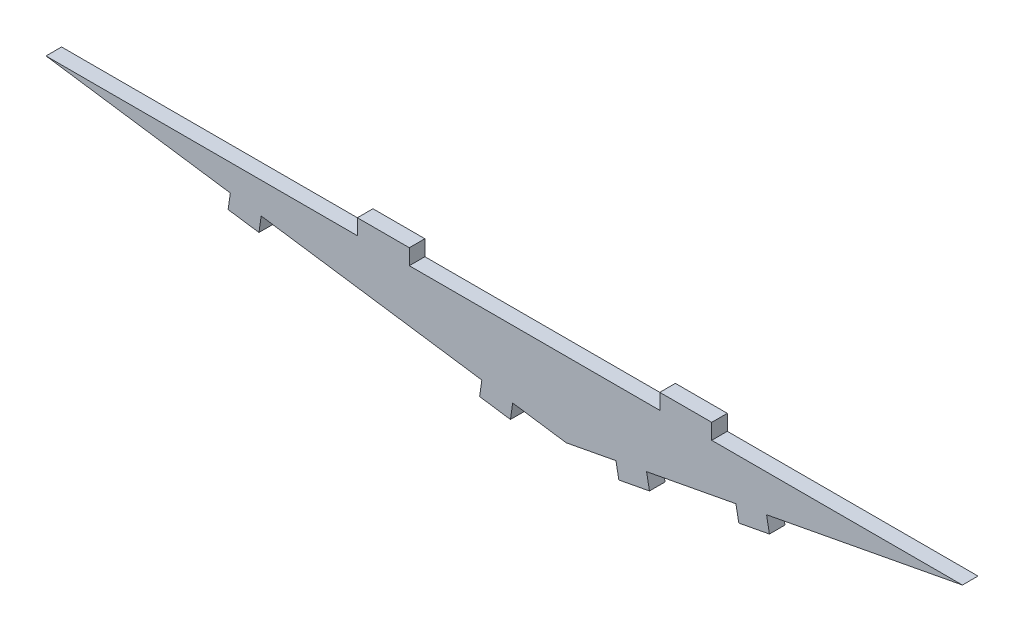
SolidWorks part; units mm, degrees
ref_plane "Front Plane" through (0, 0, 0) normal (0, 0, 1) x (1, 0, 0)
ref_plane "Top Plane" through (0, 0, 0) normal (0, 1, 0) x (1, 0, 0)
ref_plane "Right Plane" through (0, 0, 0) normal (1, 0, 0) x (0, 0, -1)
sketch "Sketch1" plane through (0, 0, 0) normal (0, 0, 1) x (1, 0, 0)
  line L0 (-9.6026, -1.524) -> (-28.7616, -5.1463)
  line L1 (-48.356, -8.8509) -> (-53.5934, -8.0967)
  line L3 (-9.6026, -1.524) -> (-34.1228, -1.524)
  line L4 (-43.4902, -7.9309) -> (-48.356, -8.8509)
  line L5 (-31.7566, -5.7125) -> (-40.4953, -7.3647)
  line L6 (-31.7566, -5.7125) -> (-31.4734, -7.21)
  line L7 (-43.4902, -7.9309) -> (-43.2071, -9.4284)
  line L8 (-28.7616, -5.1463) -> (-28.4785, -6.6437)
  line L9 (-40.4953, -7.3647) -> (-40.2122, -8.8622)
  line L10 (-56.6102, -7.6623) -> (-78.1919, -4.5547)
  line L11 (-31.4734, -7.21) -> (-28.4785, -6.6437)
  line L12 (-81.2088, -4.1203) -> (-99.2391, -1.524)
  line L14 (-81.2088, -4.1203) -> (-81.426, -5.6287)
  line L15 (-56.6102, -7.6623) -> (-56.8274, -9.1707)
  line L16 (-78.1919, -4.5547) -> (-78.4091, -6.0631)
  line L17 (-53.5934, -8.0967) -> (-53.8106, -9.6051)
  line L18 (-63.7031, -1.524) -> (-63.7031, 0)
  line L19 (-81.426, -5.6287) -> (-78.4091, -6.0631)
  line L20 (-43.2071, -9.4284) -> (-40.2122, -8.8622)
  line L21 (-56.8274, -9.1707) -> (-53.8106, -9.6051)
  line L22 (-34.1228, -1.524) -> (-34.1228, 0)
  line L23 (-68.7831, -1.524) -> (-68.7831, 0)
  line L24 (-39.2028, -1.524) -> (-39.2028, 0)
  line L25 (-68.7831, -1.524) -> (-99.2391, -1.524)
  line L26 (-63.7031, 0) -> (-68.7831, 0)
  line L27 (-39.2028, -1.524) -> (-63.7031, -1.524)
  line L28 (-34.1228, 0) -> (-39.2028, 0)
extrude "Boss-Extrude1" add sketch "Sketch1" against normal blind 1.524
